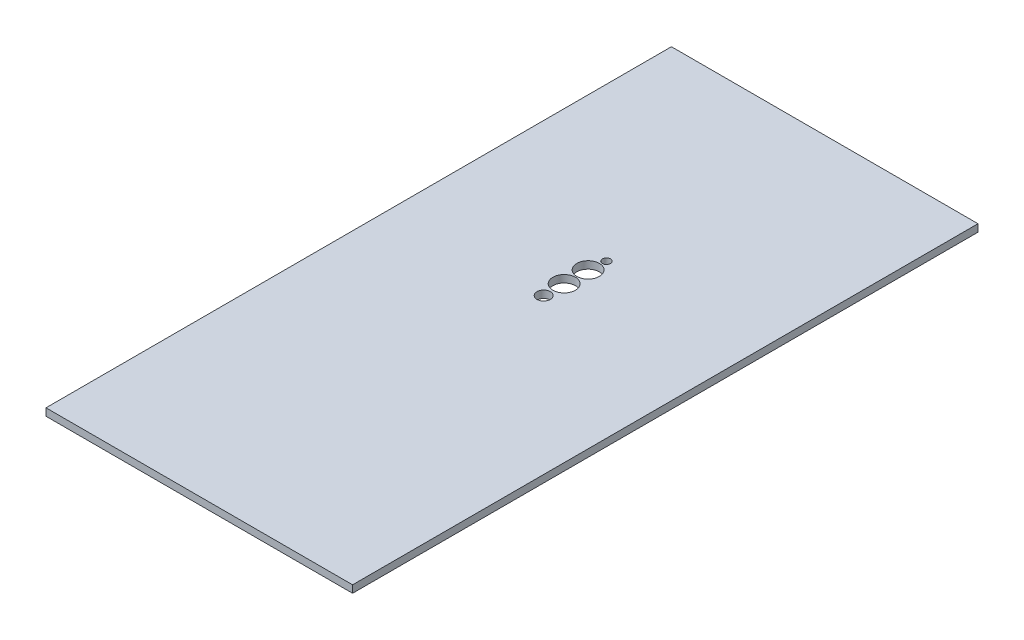
SolidWorks part; units mm, degrees
ref_plane "Plano frontal" through (0, 0, 0) normal (0, 0, 1) x (1, 0, 0)
ref_plane "Plano superior" through (0, 0, 0) normal (0, 1, 0) x (1, 0, 0)
ref_plane "Plano direito" through (0, 0, 0) normal (1, 0, 0) x (0, 0, -1)
sketch "Esboço1" plane through (0, 0, 0) normal (0, 1, 0) x (1, 0, 0)
  line L1 (0, 0) -> (250, 0)
  line L2 (0, 0) -> (0, -475)
  line L3 (0, -475) -> (250, -475)
  line L4 (250, 0) -> (250, -475)
extrude "Ressalto-extrusão1" add sketch "Esboço1" along normal blind 6
sketch "Esboço2" plane through (0, 0, 0) normal (0, 0, -1) x (-1, 0, 0)
  line L1 (-250, 6) -> (0, 6)
  line L2 (-250, 6) -> (-250, 0)
  line L3 (-250, 0) -> (0, 0)
  line L4 (0, 6) -> (0, 0)
extrude "Ressalto-extrusão2" add sketch "Esboço2" along normal blind 25
sketch "Esboço3" plane through (0, 0, -25) normal (0, 0, -1) x (-1, 0, 0)
  line L1 (-250, 6) -> (0, 6)
  line L2 (-250, 6) -> (-250, 0)
  line L3 (-250, 0) -> (0, 0)
  line L4 (0, 6) -> (0, 0)
extrude "Ressalto-extrusão4" add sketch "Esboço3" along normal blind 80
sketch "Esboço4" plane through (0, 0, -105) normal (0, 0, -1) x (-1, 0, 0)
  line L1 (-250, 6) -> (0, 6)
  line L2 (-250, 6) -> (-250, 0)
  line L3 (-250, 0) -> (0, 0)
  line L4 (0, 6) -> (0, 0)
extrude "Corte-extrusão1" cut sketch "Esboço4" against normal blind 70
sketch "Esboço5" plane through (0, 6, 0) normal (0, 1, 0) x (1, 0, 0)
  circle A1 centre (125, -142.9736) radius 3.3
  circle A2 centre (123.646, -156.5888) radius 9.2
  circle A4 centre (123.646, -192.7962) radius 5.5
  circle A5 centre (123.646, -176.1217) radius 9.2
  point P12 (124.5475, -204.2184)
  point P16 (125, -180.6835)
  point P17 (125, -183.2562)
  point P18 (125, -202.2174)
  point P19 (124.9286, -218.7966)
  point P20 (124.5475, -202.7891)
extrude "Corte-extrusão3" cut sketch "Esboço5" against normal through all
